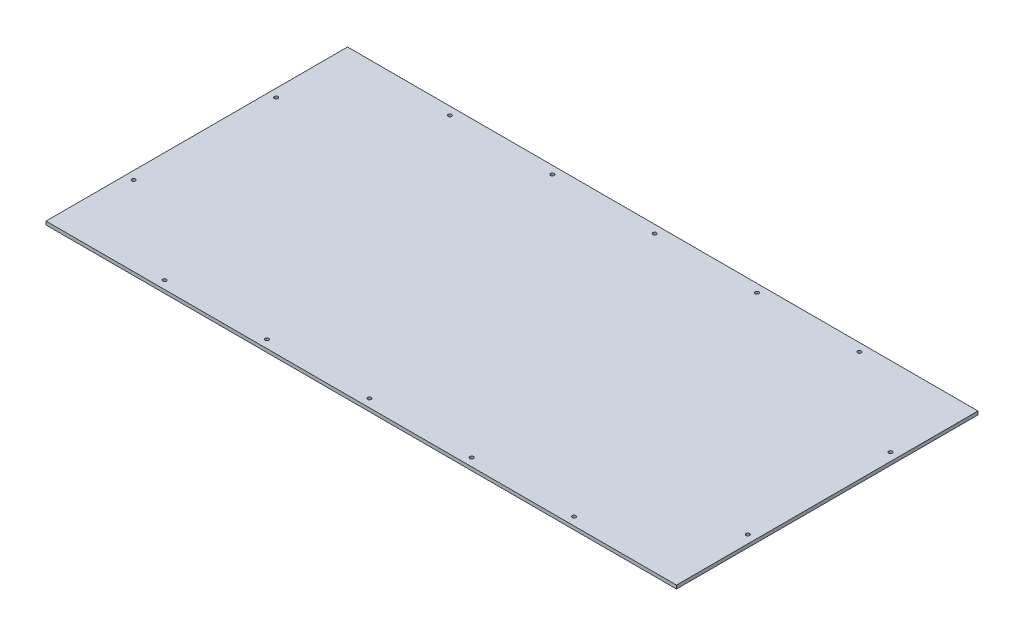
SolidWorks part; units mm, degrees
ref_plane "Front Plane" through (0, 0, 0) normal (0, 0, 1) x (1, 0, 0)
ref_plane "Top Plane" through (0, 0, 0) normal (0, 1, 0) x (1, 0, 0)
ref_plane "Right Plane" through (0, 0, 0) normal (1, 0, 0) x (0, 0, -1)
sketch "Sketch1" plane through (0, 0, 0) normal (0, 1, 0) x (1, 0, 0)
  line L0 (0, 139.7) -> (0, -139.7) construction
  line L1 (-292.1, 139.7) -> (292.1, 139.7)
  line L2 (-292.1, 139.7) -> (-292.1, -139.7)
  line L3 (-292.1, -139.7) -> (292.1, -139.7)
  line L4 (292.1, 139.7) -> (292.1, -139.7)
  line L5 (-292.1, 139.7) -> (292.1, -139.7) construction
  line L6 (-292.1, -139.7) -> (292.1, 139.7) construction
  line L7 (-284.6, 132.2) -> (284.6, 132.2) construction
  line L8 (-284.6, 132.2) -> (-284.6, -132.2) construction
  line L9 (-284.6, -132.2) -> (284.6, -132.2) construction
  line L10 (284.6, 132.2) -> (284.6, -132.2) construction
  line L11 (-284.6, 132.2) -> (284.6, -132.2) construction
  line L12 (-284.6, -132.2) -> (284.6, 132.2) construction
  line L13 (-292.1, 0) -> (292.1, 0) construction
  line L14 (284.6, 132.2) -> (284.6, -132.2) construction
  circle A0 centre (-284.6, 66.1) radius 1.65
  circle A1 centre (-189.7333, 132.2) radius 1.65
  circle A2 centre (-94.8667, 132.2) radius 1.65
  circle A3 centre (-284.6, -66.1) radius 1.65
  circle A4 centre (-94.8667, -132.2) radius 1.65
  circle A5 centre (-189.7333, -132.2) radius 1.65
  circle A6 centre (189.7333, -132.2) radius 1.65
  circle A7 centre (94.8667, -132.2) radius 1.65
  circle A8 centre (94.8667, 132.2) radius 1.65
  circle A9 centre (189.7333, 132.2) radius 1.65
  circle A10 centre (284.6, -66.1) radius 1.65
  circle A11 centre (284.6, 66.1) radius 1.65
  circle A12 centre (0, 132.2) radius 1.65
  circle A13 centre (0, -132.2) radius 1.65
  point P0 (0, 0)
  point P6 (0, 0)
  dimension "D5" = 3.3
  dimension "D6" = 3.3
  dimension "D7" = 3.3
  dimension "D12" = 3.3
  dimension "D13" = 3.3
  dimension "D1" = 584.2
  dimension "D2" = 279.4
  dimension "D3" = 7.5
  dimension "D4" = 7.5
  dimension "D8" = 66.1
  dimension "D9" = 94.8667
  dimension "D10" = 94.8667
  dimension "D11" = 94.8667
extrude "Boss-Extrude1" add sketch "Sketch1" along normal blind 3.175
equation "\"D6@Sketch1\"=\"D5@Sketch1\""
equation "\"D7@Sketch1\"=\"D5@Sketch1\""
equation "\"D10@Sketch1\"=\"D9@Sketch1\""
equation "\"D12@Sketch1\"=\"D5@Sketch1\""
equation "\"D13@Sketch1\"=\"D5@Sketch1\""
